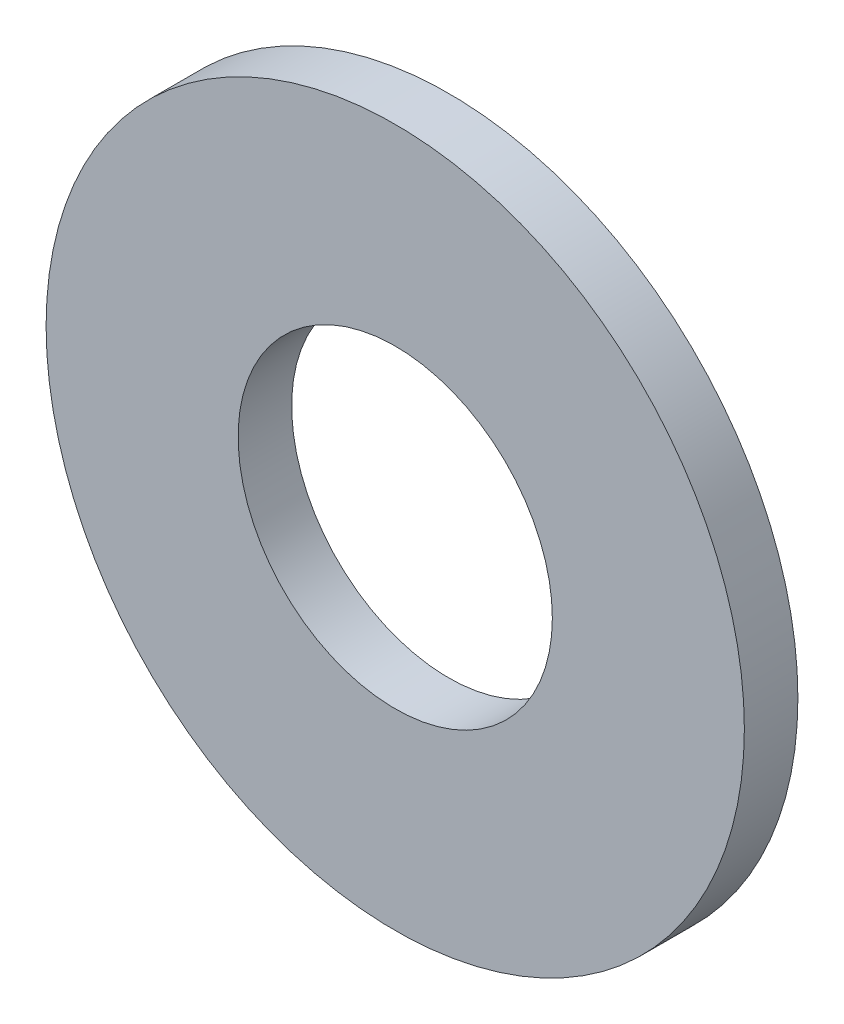
SolidWorks part; units mm, degrees
ref_plane "Plan de face" through (0, 0, 0) normal (0, 0, 1) x (1, 0, 0)
ref_plane "Plan de dessus" through (0, 0, 0) normal (0, 1, 0) x (1, 0, 0)
ref_plane "Plan de droite" through (0, 0, 0) normal (1, 0, 0) x (0, 0, -1)
sketch "Esquisse1" plane through (0, 0, 0) normal (0, 0, 1) x (1, 0, 0)
  circle A0 centre (0, 0) radius 6.75
  circle A1 centre (0, 0) radius 15
  dimension "D1" = 13.5
  dimension "D2" = 30
extrude "Boss.-Extru.1" add sketch "Esquisse1" along normal mid plane 2.3
